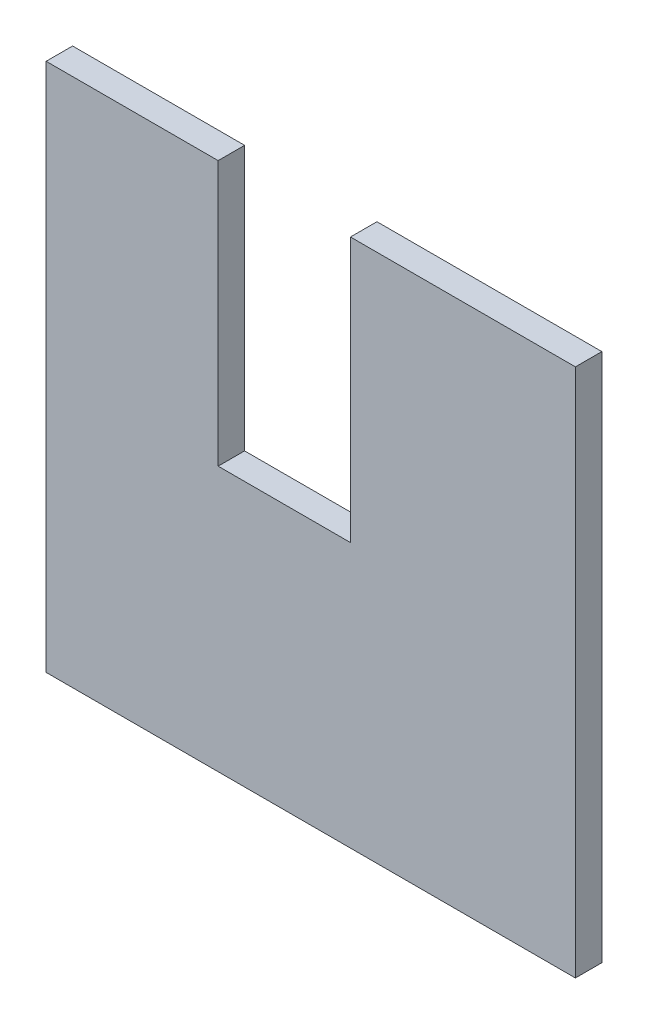
SolidWorks part; units mm, degrees
material "Balsa"
ref_plane "Front Plane" through (0, 0, 0) normal (0, 0, 1) x (1, 0, 0)
ref_plane "Top Plane" through (0, 0, 0) normal (0, 1, 0) x (1, 0, 0)
ref_plane "Right Plane" through (0, 0, 0) normal (1, 0, 0) x (0, 0, -1)
sketch "Sketch2" plane through (0, 0, 0) normal (0, 0, 1) x (1, 0, 0)
  line L0 (-90, -100) -> (110, -100)
  line L1 (-90, -100) -> (-90, 100)
  line L2 (110, -100) -> (110, 100)
  line L3 (-90, 100) -> (110, 100)
  line L4 (110, 0) -> (-90, 0) construction
  line L5 (0, -100) -> (0, 100) construction
  line L8 (-25, 0) -> (25, 0)
  line L9 (-90, 0) -> (110, 0) construction
  line L10 (-25, 0) -> (-25, 100)
  line L12 (25, 0) -> (25, 100)
  point P0 (0, 0)
  point P1 (0, 0)
  dimension "D1" = 200
  dimension "D2" = 200
  dimension "D3" = 50
  dimension "D4" = 25
  dimension "D6" = 90
  dimension "D5" = 100
extrude "Boss-Extrude1" add sketch "Sketch2" along normal blind 10 contours L12 L8 L10 L3 L1 L0 L2
